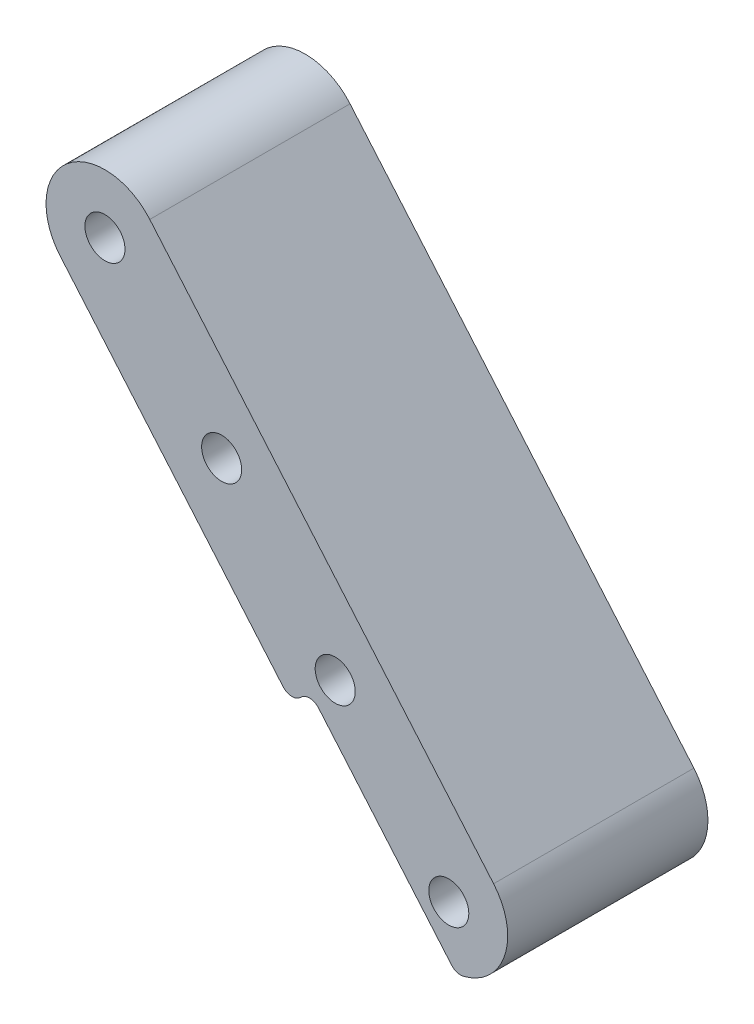
SolidWorks part; units mm, degrees
ref_plane "前视基准面" through (0, 0, 0) normal (0, 0, 1) x (1, 0, 0)
ref_plane "上视基准面" through (0, 0, 0) normal (0, 1, 0) x (1, 0, 0)
ref_plane "右视基准面" through (0, 0, 0) normal (1, 0, 0) x (0, 0, -1)
other "Configuration Table"
sketch "草图1" plane through (0, 0, 0) normal (0, 0, 1) x (1, 0, 0)
  line L15 (44.7669, -56.8983) -> (91.6346, -112.753)
  line L20 (91.2983, -112.1282) -> (90.4181, -110.3506)
  line L22 (33.7211, -44.8147) -> (92.0987, -113.3062) construction
  line L23 (41.3317, -38.3279) -> (99.7094, -106.8194)
  line L24 (26.1105, -51.3015) -> (84.4881, -119.793)
  circle A47 centre (33.7211, -44.8147) radius 3.4
  circle A48 centre (53.5315, -67.3435) radius 3.4
  circle A50 centre (72.8151, -90.3249) radius 3.4
  circle A52 centre (92.0987, -113.3062) radius 3.4
  arc A61 (91.2983, -112.1282) -> (91.6346, -112.753) centre (289.5975, -5.8154) ccw
  arc A66 (44.7669, -56.8983) -> (28.5093, -39.4853) centre (-127.5931, -201.5255) ccw
  arc A67 (41.3317, -38.3279) -> (26.1105, -51.3015) centre (33.7211, -44.8147) ccw
  arc A68 (84.4881, -119.793) -> (99.7094, -106.8194) centre (92.0987, -113.3062) ccw
  point P0 (62.9099, -79.0605)
  dimension "D1" = 10
  dimension "D2" = 6.8
  dimension "D3" = 6.8
  dimension "D4" = 6.8
  dimension "D8" = 6.8
  dimension "D5" = 30
  dimension "D6" = 30
  dimension "D7" = 30
extrude "凸台-拉伸3" add sketch "草图1" along normal blind 34
sketch "草图2" plane through (0, 0, 34) normal (0, 0, 1) x (1, 0, 0)
  line L0 (93.3304, -123.2301) -> (68.6806, -94.3097)
  line L1 (68.6806, -94.3097) -> (65.2558, -97.2288)
  line L2 (26.1105, -51.3015) -> (84.4881, -119.793)
  line L3 (99.7094, -106.8194) -> (41.3317, -38.3279)
  line L4 (26.1105, -51.3015) -> (84.4881, -119.793)
  line L5 (99.7094, -106.8194) -> (41.3317, -38.3279)
  arc A2 (84.4881, -119.793) -> (99.7094, -106.8194) centre (92.0987, -113.3062) ccw
  arc A3 (41.3317, -38.3279) -> (26.1105, -51.3015) centre (33.7211, -44.8147) ccw
  arc A4 (84.4881, -119.793) -> (99.7094, -106.8194) centre (92.0987, -113.3062) ccw
  arc A5 (41.3317, -38.3279) -> (26.1105, -51.3015) centre (33.7211, -44.8147) ccw
  line M9 (26.1105, -51.3015) -> (84.4881, -119.793)
  arc M10 (84.4881, -119.793) -> (99.7094, -106.8194) centre (92.0987, -113.3062) ccw
  dimension "D2" = 38
  dimension "D3" = 4.5
  dimension "D1" = 0
extrude "切除-拉伸1" cut sketch "草图2" against normal through all contours L0 L1 M9 M10
fillet "圆角1" radius 2 3 edges at (65.2558, -97.2288, 17) (93.3304, -123.2301, 17) (68.6806, -94.3097, 17)
